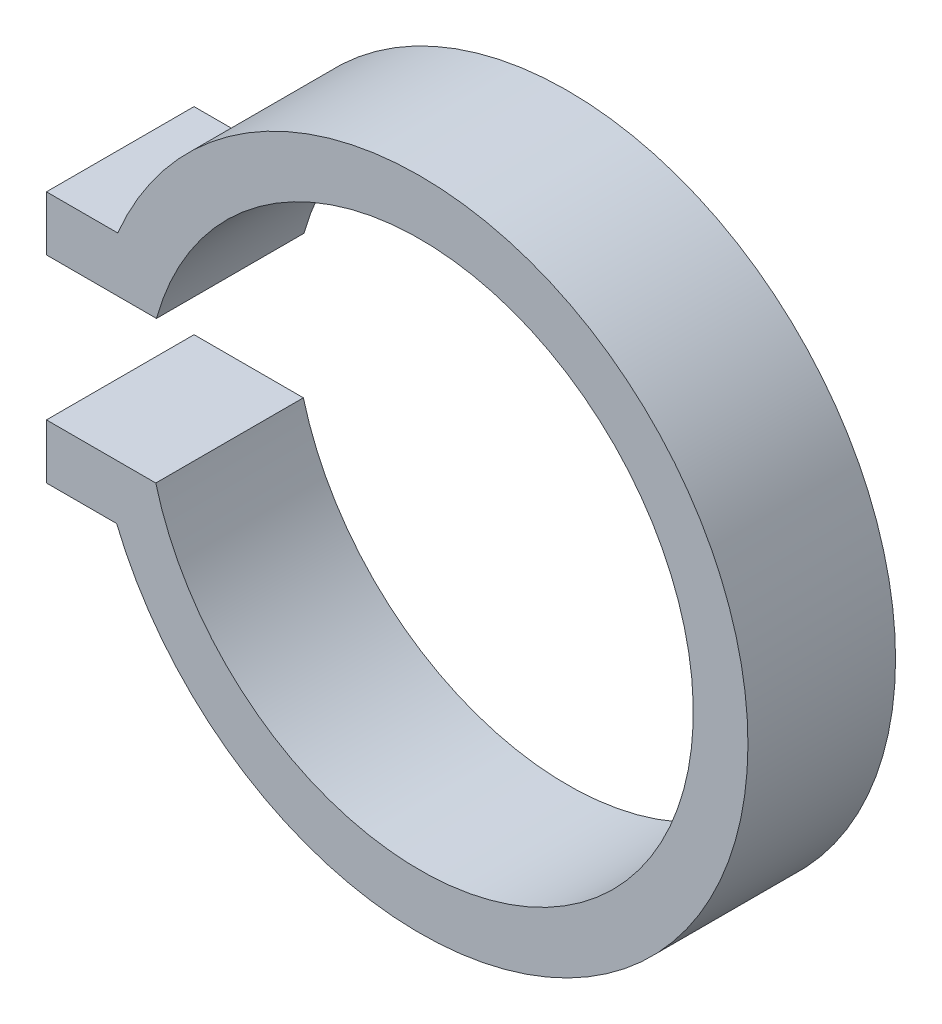
SolidWorks part; units mm, degrees
ref_plane "Front Plane" through (0, 0, 0) normal (0, 0, 1) x (1, 0, 0)
ref_plane "Top Plane" through (0, 0, 0) normal (0, 1, 0) x (1, 0, 0)
ref_plane "Right Plane" through (0, 0, 0) normal (1, 0, 0) x (0, 0, -1)
sketch "Sketch1" plane through (0, 0, 0) normal (0, 0, 1) x (1, 0, 0)
  line L0 (-0.3013, 2.5108) -> (-0.3013, -49997.4892) construction
  line L1 (-2.6782, 0.2378) -> (49997.3218, 0.2378) construction
  line L2 (-68.3263, 23.3041) -> (-55.2894, 23.3041)
  line L3 (-68.3263, -22.8285) -> (-55.2894, -22.8285)
  line L4 (-48.1975, 13.3041) -> (-68.3263, 13.3041)
  line L5 (-48.3263, -12.8285) -> (-68.3263, -12.8285)
  line L6 (-68.3263, 23.3041) -> (-68.3263, 13.3041)
  line L7 (-68.3263, -12.8285) -> (-68.3263, -22.8285)
  arc A0 (-55.4875, -22.8285) -> (-55.2894, 23.3041) centre (0, 0) ccw
  arc A1 (-48.3263, -12.8285) -> (-48.1975, 13.3041) centre (0, 0) ccw
  arc A2 (-46.2396, -19.0237) -> (-46.0745, 19.4201) centre (0, 0) ccw construction
  dimension "D2" = 50
  dimension "D3" = 10
  dimension "D4" = 10
  dimension "D5" = 20
  dimension "D1" = 10
extrude "Boss-Extrude1" add sketch "Sketch1" along normal blind 27
